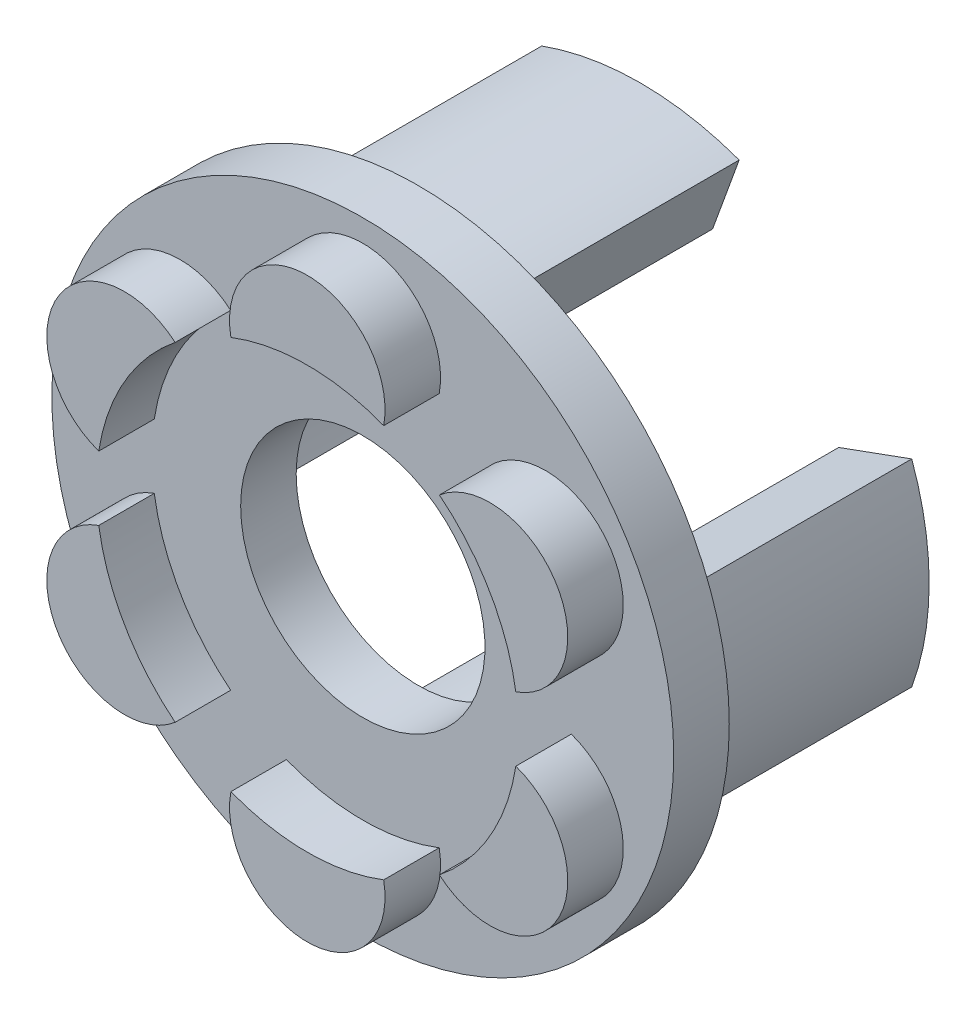
SolidWorks part; units mm, degrees
ref_plane "前视基准面" through (0, 0, 0) normal (0, 0, 1) x (1, 0, 0)
ref_plane "上视基准面" through (0, 0, 0) normal (0, 1, 0) x (1, 0, 0)
ref_plane "右视基准面" through (0, 0, 0) normal (1, 0, 0) x (0, 0, -1)
sketch "草图1" plane through (0, 0, 0) normal (0, 0, 1) x (1, 0, 0)
  circle A0 centre (0, 0) radius 28
  dimension "D1" = 56
extrude "凸台-拉伸1" add sketch "草图1" along normal blind 5
sketch "草图2" plane through (0, 0, 0) normal (0, 0, -1) x (-1, 0, 0)
  line L0 (-6.4984, 17.8542) -> (-8.8925, 24.432)
  line L1 (0, 19) -> (0, 26) construction
  line L2 (6.4984, 17.8542) -> (8.8925, 24.432)
  line L3 (0, 0) -> (-6.4984, 17.8542) construction
  line L4 (0, 0) -> (0, 19) construction
  line L5 (0, 0) -> (6.4984, 17.8542) construction
  line L6 (17.8542, 6.4984) -> (24.432, 8.8925)
  line L7 (17.8542, -6.4984) -> (24.432, -8.8925)
  line L8 (6.4984, -17.8542) -> (8.8925, -24.432)
  line L9 (-6.4984, -17.8542) -> (-8.8925, -24.432)
  line L10 (-17.8542, -6.4984) -> (-24.432, -8.8925)
  line L11 (-17.8542, 6.4984) -> (-24.432, 8.8925)
  arc A0 (8.8925, 24.432) -> (-8.8925, 24.432) centre (0, 0) ccw
  arc A1 (6.4984, 17.8542) -> (-6.4984, 17.8542) centre (0, 0) ccw
  arc A2 (-8.8925, 24.432) -> (8.8925, 24.432) centre (0, 0) ccw construction
  arc A3 (-6.4984, 17.8542) -> (6.4984, 17.8542) centre (0, 0) ccw construction
  arc A4 (24.432, -8.8925) -> (24.432, 8.8925) centre (0, 0) ccw
  arc A5 (17.8542, -6.4984) -> (17.8542, 6.4984) centre (0, 0) ccw
  arc A6 (-8.8925, -24.432) -> (8.8925, -24.432) centre (0, 0) ccw
  arc A7 (-6.4984, -17.8542) -> (6.4984, -17.8542) centre (0, 0) ccw
  arc A8 (-24.432, 8.8925) -> (-24.432, -8.8925) centre (0, 0) ccw
  arc A9 (-17.8542, 6.4984) -> (-17.8542, -6.4984) centre (0, 0) ccw
  point P23 (0, 0)
  dimension "D1" = 52
  dimension "D2" = 38
  dimension "D4" = 40
  dimension "D3" = 4
extrude "凸台-拉伸2" add sketch "草图2" along normal blind 20
sketch "草图3" plane through (0, 0, 0) normal (0, 0, -1) x (-1, 0, 0)
  circle A0 centre (0, 0) radius 11
  dimension "D1" = 22
extrude "切除-拉伸1" cut sketch "草图3" against normal blind 5
sketch "草图4" plane through (0, 0, 5) normal (0, 0, 1) x (1, 0, 0)
  arc A0 (-18.7779, 2.8968) -> (-18.7779, -2.8968) centre (0, 0) ccw construction
  arc A1 (6.8802, 17.7105) -> (-6.8802, 17.7105) centre (0, 19) ccw
  arc A2 (18.7779, 2.8968) -> (11.8977, 14.8137) centre (16.4545, 9.5) ccw construction
  arc A3 (18.7779, -2.8968) -> (11.8977, -14.8137) centre (16.4545, -9.5) ccw construction
  arc A4 (-6.8802, -17.7105) -> (6.8802, -17.7105) centre (0, -19) ccw construction
  arc A5 (-11.8977, -14.8137) -> (-18.7779, -2.8968) centre (-16.4545, -9.5) ccw construction
  arc A6 (-11.8977, 14.8137) -> (-18.7779, 2.8968) centre (-16.4545, 9.5) ccw construction
  arc A8 (-6.8802, 17.7105) -> (6.8802, 17.7105) centre (0, 0) cw
  arc A9 (-6.8802, 17.7105) -> (6.8802, 17.7105) centre (0, 19) ccw construction
  arc A10 (-18.7779, 2.8968) -> (-11.8977, 14.8137) centre (-16.4545, 9.5) ccw construction
  arc A11 (-11.8977, 14.8137) -> (-18.7779, 2.8968) centre (0, 0) ccw construction
  arc A12 (-18.7779, -2.8968) -> (-11.8977, -14.8137) centre (-16.4545, -9.5) ccw construction
  arc A13 (-18.7779, -2.8968) -> (-11.8977, -14.8137) centre (0, 0) ccw construction
  arc A14 (-11.8977, -14.8137) -> (-6.8802, -17.7105) centre (0, 0) ccw construction
  arc A15 (6.8802, -17.7105) -> (-6.8802, -17.7105) centre (0, -19) ccw construction
  arc A16 (-6.8802, -17.7105) -> (6.8802, -17.7105) centre (0, 0) ccw construction
  arc A17 (6.8802, -17.7105) -> (11.8977, -14.8137) centre (0, 0) ccw construction
  arc A18 (11.8977, -14.8137) -> (18.7779, -2.8968) centre (16.4545, -9.5) ccw construction
  arc A19 (11.8977, -14.8137) -> (18.7779, -2.8968) centre (0, 0) ccw construction
  arc A20 (18.7779, -2.8968) -> (18.7779, 2.8968) centre (0, 0) ccw construction
  arc A21 (11.8977, 14.8137) -> (18.7779, 2.8968) centre (16.4545, 9.5) ccw construction
  arc A22 (18.7779, 2.8968) -> (11.8977, 14.8137) centre (0, 0) ccw construction
  arc A23 (11.8977, 14.8137) -> (-11.8977, 14.8137) centre (0, 0) ccw construction
  arc A24 (18.7779, 2.8968) -> (11.8977, 14.8137) centre (16.4545, 9.5) ccw
  arc A25 (11.8977, 14.8137) -> (18.7779, 2.8968) centre (0, 0) cw
  arc A26 (11.8977, -14.8137) -> (18.7779, -2.8968) centre (16.4545, -9.5) ccw
  arc A27 (18.7779, -2.8968) -> (11.8977, -14.8137) centre (0, 0) cw
  arc A28 (-6.8802, -17.7105) -> (6.8802, -17.7105) centre (0, -19) ccw
  arc A29 (6.8802, -17.7105) -> (-6.8802, -17.7105) centre (0, 0) cw
  arc A30 (-18.7779, -2.8968) -> (-11.8977, -14.8137) centre (-16.4545, -9.5) ccw
  arc A31 (-11.8977, -14.8137) -> (-18.7779, -2.8968) centre (0, 0) cw
  arc A32 (-11.8977, 14.8137) -> (-18.7779, 2.8968) centre (-16.4545, 9.5) ccw
  arc A33 (-18.7779, 2.8968) -> (-11.8977, 14.8137) centre (0, 0) cw
  point P3 (0, 0)
  point P12 (0, 0)
  point P40 (0, 0)
  dimension "D2" = 14
  dimension "D1" = 38
  dimension "D3" = 6
extrude "凸台-拉伸4" add sketch "草图4" along normal blind 5
